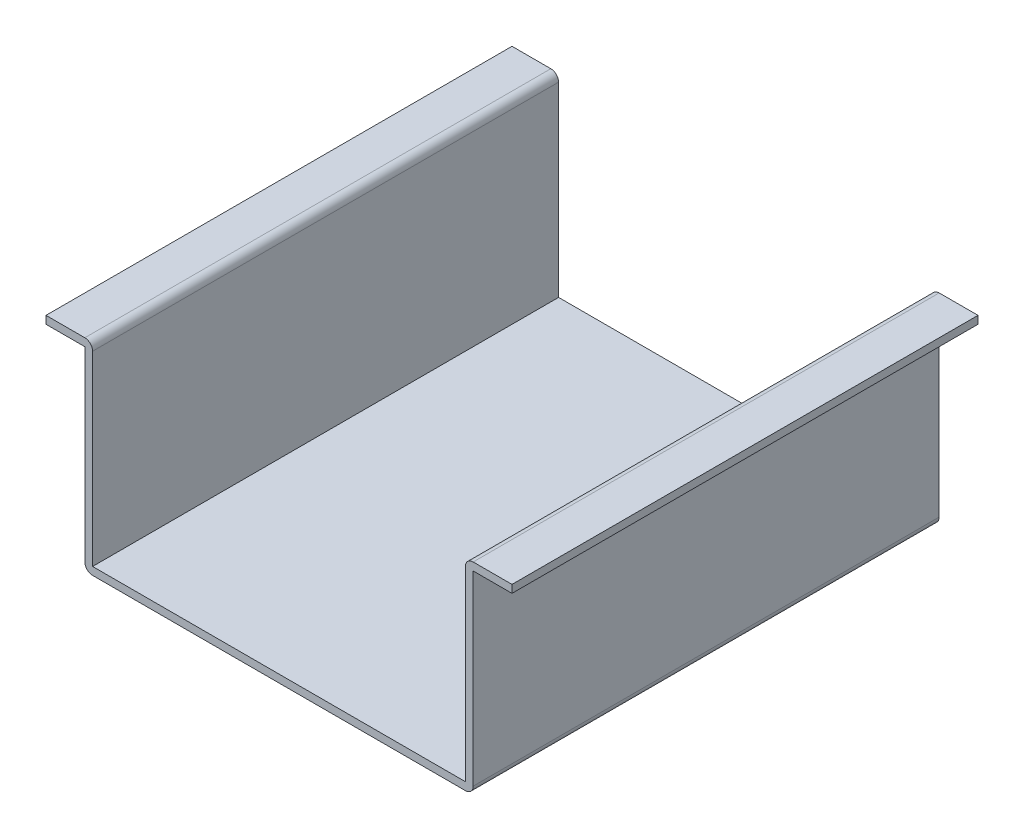
SolidWorks part; units mm, degrees
ref_plane "前视基准面" through (0, 0, 0) normal (0, 0, 1) x (1, 0, 0)
ref_plane "上视基准面" through (0, 0, 0) normal (0, 1, 0) x (1, 0, 0)
ref_plane "右视基准面" through (0, 0, 0) normal (1, 0, 0) x (0, 0, -1)
ref_plane "基准面4" through (0, 52, 0) normal (0, 1, 0) x (1, 0, 0)
sketch "草图1" plane through (0, 52, 0) normal (0, 1, 0) x (1, 0, 0)
  line L0 (-60, -60) -> (60, -60)
  line L1 (60, -60) -> (60, 60)
  line L2 (60, 60) -> (-60, 60)
  line L3 (-60, 60) -> (-60, -60)
  dimension "D1" = 120
  dimension "D2" = 120
  dimension "D3" = 60
  dimension "D4" = 60
extrude "凸台-拉伸1" add sketch "草图1" against normal blind 52
sketch "草图2" plane through (0, 0, -60) normal (0, 0, -1) x (-1, 0, 0)
  line L0 (-48, 52) -> (-48, 2)
  line L1 (-48, 2) -> (48, 2)
  line L2 (48, 2) -> (48, 52)
  line L3 (48, 52) -> (-48, 52)
  line L4 (0, 0) -> (0, 52) construction
  line L5 (-60, 52) -> (60, 52) construction
  dimension "D1" = 2
  dimension "D2" = 48
extrude "切除-拉伸1" cut sketch "草图2" against normal through all
sketch "草图4" plane through (0, 0, 60) normal (0, 0, 1) x (1, 0, 0)
  line L0 (60, 50) -> (50, 50)
  line L1 (50, 50) -> (50, 0)
  line L2 (50, 0) -> (60, 0)
  line L3 (60, 0) -> (60, 50)
  line L4 (60, 0) -> (60, 52) construction
  line L5 (60, 52) -> (48, 52) construction
  line L6 (60, 0) -> (-60, 0) construction
  dimension "D1" = 2
  dimension "D2" = 10
extrude "切除-拉伸2" cut sketch "草图4" against normal through all
sketch "草图5" plane through (0, 0, -60) normal (0, 0, -1) x (-1, 0, 0)
  line L0 (60, 50) -> (50, 50)
  line L1 (50, 50) -> (50, 0)
  line L2 (50, 0) -> (60, 0)
  line L3 (60, 0) -> (60, 50)
  line L4 (60, 0) -> (60, 52) construction
  line L5 (48, 52) -> (60, 52) construction
  line L6 (48, 2) -> (48, 52) construction
  line L7 (-50, 0) -> (60, 0) construction
  dimension "D1" = 2
  dimension "D2" = 2
extrude "切除-拉伸3" cut sketch "草图5" against normal through all
fillet "圆角1" radius 2 4 edges at (48, 52, 0) (-50, 0, 0) (-48, 52, 0) (50, 0, 0)
